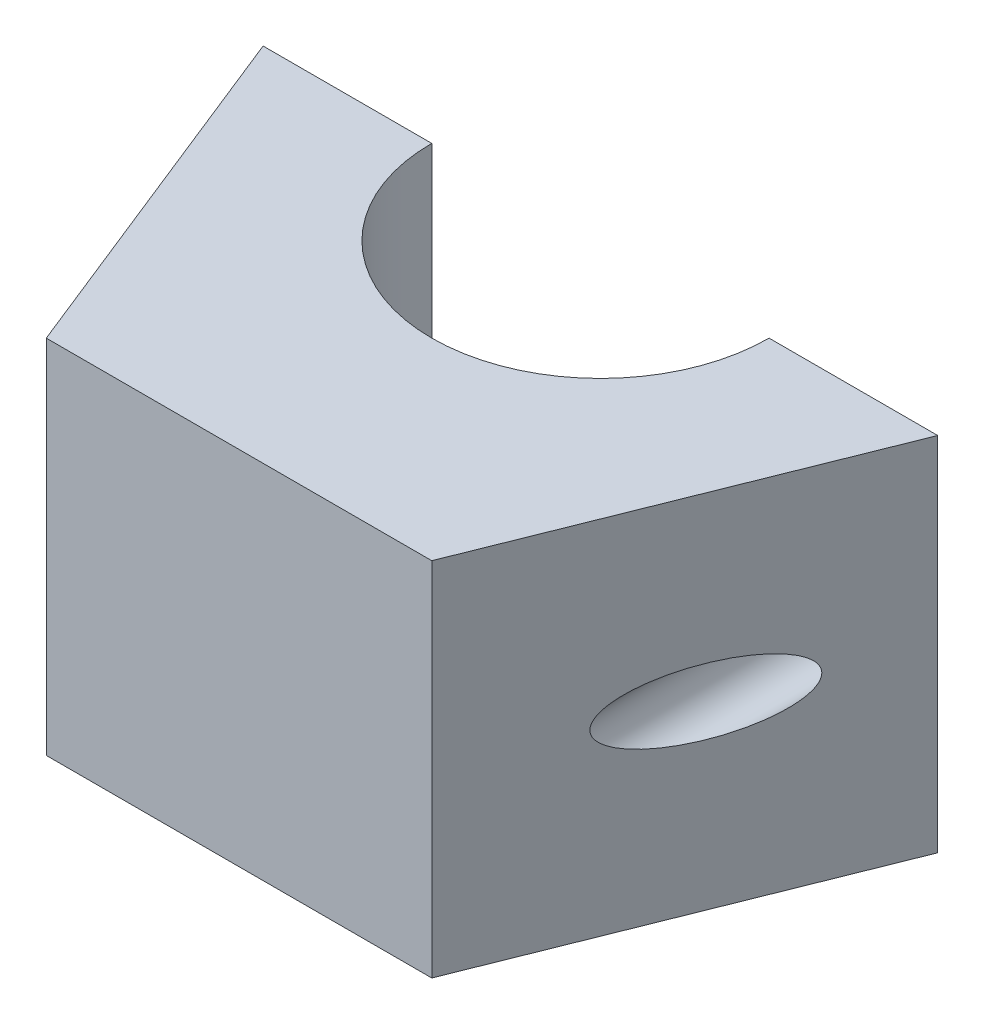
SolidWorks part; units mm, degrees
ref_plane "Front Plane" through (0, 0, 0) normal (0, 0, 1) x (1, 0, 0)
ref_plane "Top Plane" through (0, 0, 0) normal (0, 1, 0) x (1, 0, 0)
ref_plane "Right Plane" through (0, 0, 0) normal (1, 0, 0) x (0, 0, -1)
sketch "Sketch1" plane through (0, 0, 0) normal (0, 1, 0) x (1, 0, 0)
  line L1 (-34.8162, 18.0331) -> (5.1838, 18.0331)
  line L2 (-34.8162, 18.0331) -> (-34.8162, -11.9669)
  line L3 (-34.8162, -11.9669) -> (5.1838, -11.9669)
  line L4 (5.1838, 18.0331) -> (5.1838, -11.9669)
  line L5 (-14.8162, -11.9669) -> (-14.8162, 18.0331) construction
  line L6 (-34.8162, 3.0331) -> (5.1838, 3.0331) construction
  point P0 (-14.8162, 3.0331)
  dimension "D1" = 40
  dimension "D2" = 30
extrude "Boss-Extrude1" add sketch "Sketch1" along normal blind 15
sketch "Sketch2" plane through (0, 15, 0) normal (0, 1, 0) x (1, 0, 0)
  line L0 (-34.8162, 3.0331) -> (5.1838, 3.0331) construction
  line L1 (-14.8162, 18.0331) -> (-14.8162, -11.9669) construction
  line L2 (-28.8162, 18.0331) -> (-28.8162, -11.9669)
  line L3 (-0.8162, 18.0331) -> (-0.8162, -11.9669)
  line L4 (5.1838, -11.9669) -> (5.1838, 18.0331)
  line L5 (5.1838, 18.0331) -> (-34.8162, 18.0331)
  line L6 (-34.8162, 18.0331) -> (-34.8162, -11.9669)
  line L7 (-34.8162, -11.9669) -> (5.1838, -11.9669)
  line L8 (5.1838, -11.9669) -> (5.1838, 18.0331)
  line L9 (5.1838, 18.0331) -> (-34.8162, 18.0331)
  line L10 (-34.8162, 18.0331) -> (-34.8162, -11.9669)
  line L11 (-34.8162, -11.9669) -> (5.1838, -11.9669)
  line L12 (-34.8162, 18.0331) -> (-28.8162, 3.0331)
  line L13 (-28.8162, 3.0331) -> (-22.8162, -11.9669)
  line L14 (5.1838, 18.0331) -> (-0.8162, 3.0331)
  line L15 (-0.8162, 3.0331) -> (-6.8162, -11.9669)
  line L16 (-28.8162, 3.0331) -> (-21.8162, 3.0331)
  line L17 (-21.8162, 3.0331) -> (-0.8162, 3.0331)
  circle A0 centre (-14.8162, 3.0331) radius 7
  line M6 (5.1838, -11.9669) -> (5.1838, 18.0331)
  line M7 (5.1838, 18.0331) -> (-34.8162, 18.0331)
  line M8 (-34.8162, 18.0331) -> (-34.8162, -11.9669)
  line M9 (-34.8162, -11.9669) -> (5.1838, -11.9669)
  dimension "D2" = 14
  dimension "D4" = 6
  dimension "D3" = 6
  dimension "D1" = 0
extrude "Cut-Extrude1" cut sketch "Sketch2" against normal blind 15 contours L12 L2 M7 | A0 L17 L3 L2 L16 M7 | L14 L3 M7 | L14 L3 M6 M9 | L3 L15 M9 | L13 L2 M9 | L12 L2 M8 M9 | L17 A0 | L17 A0
sketch "Sketch3" plane through (0, 0, -3.0331) normal (0, 0, -1) x (-1, 0, 0)
  line L0 (3.5662, 15) -> (3.5662, 0) construction
  line L1 (0.8162, 7.5) -> (28.8162, 7.5) construction
  line L2 (14.8162, 7.5) -> (14.8162, 13.5492) construction
  line L3 (0.8162, 7.5) -> (0.8162, 15) construction
  line L4 (28.8162, 15) -> (21.8162, 15)
  line L5 (21.8162, 15) -> (21.8162, 0)
  line L6 (21.8162, 0) -> (28.8162, 0)
  line L7 (28.8162, 0) -> (28.8162, 15)
  line L8 (28.8162, 15) -> (21.8162, 15)
  line L9 (21.8162, 15) -> (21.8162, 0)
  line L10 (21.8162, 0) -> (28.8162, 0)
  line L11 (28.8162, 0) -> (28.8162, 15)
  line L12 (7.8162, 15) -> (0.8162, 15)
  line L13 (0.8162, 15) -> (0.8162, 0)
  line L14 (0.8162, 0) -> (7.8162, 0)
  line L15 (7.8162, 0) -> (7.8162, 15)
  line L16 (7.8162, 15) -> (0.8162, 15)
  line L17 (0.8162, 15) -> (0.8162, 0)
  line L18 (0.8162, 0) -> (7.8162, 0)
  line L19 (7.8162, 0) -> (7.8162, 15)
  line L20 (0.8162, 11.25) -> (3.5662, 11.25) construction
  line L21 (26.0662, 15) -> (26.0662, 0) construction
  circle A6 centre (3.5662, 7.5) radius 1.375
  circle A7 centre (26.0662, 7.5) radius 1.375
  dimension "D3" = 2.75
  dimension "D4" = 2.75
  dimension "D1" = 0
  dimension "D2" = 0
extrude "Cut-Extrude2" cut sketch "Sketch3" against normal blind 15
sketch "Sketch5" plane through (0, 0, 11.9669) normal (0, 0, 1) x (1, 0, 0)
  line L0 (-14.8162, 15) -> (-14.8162, 0) construction
  line L1 (-22.8162, 15) -> (-6.8162, 15) construction
  line L2 (-22.8162, 0) -> (-6.8162, 0) construction
  circle A0 centre (-14.8162, 7.5) radius 2
  dimension "D1" = 4
